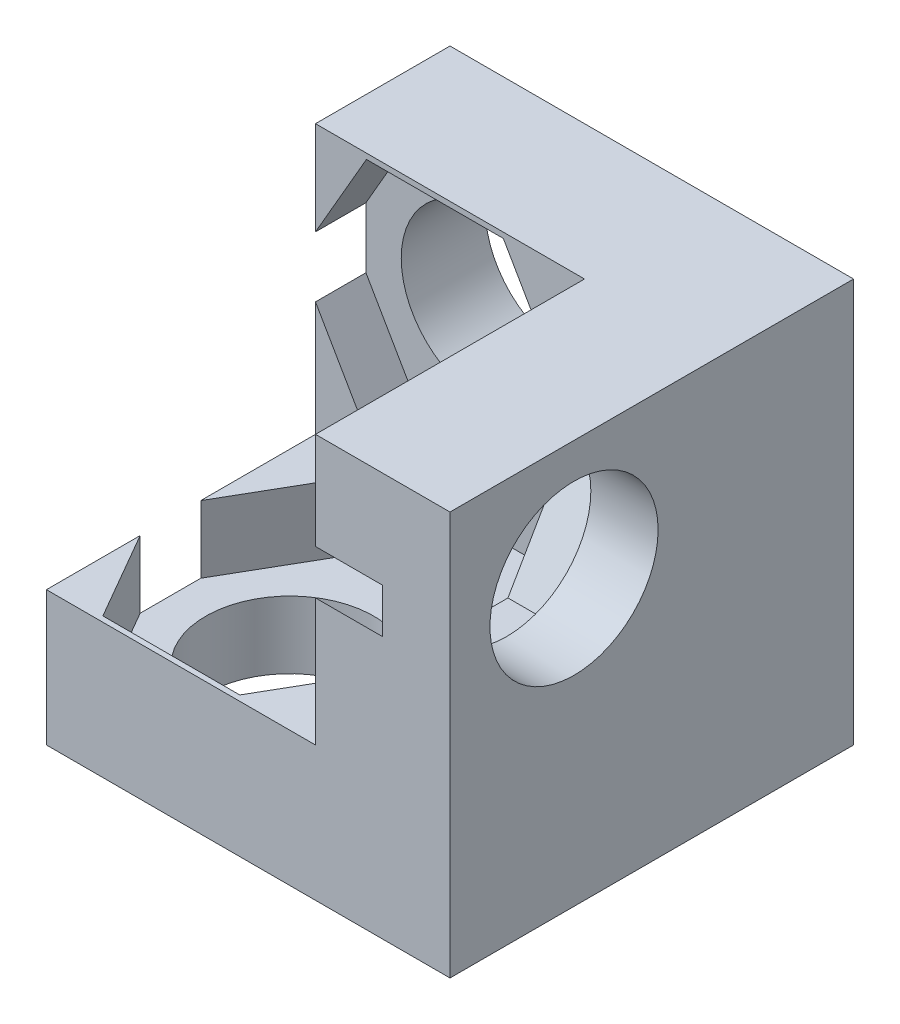
SolidWorks part; units mm, degrees
ref_plane "Front Plane" through (0, 0, 0) normal (0, 0, 1) x (1, 0, 0)
ref_plane "Top Plane" through (0, 0, 0) normal (0, 1, 0) x (1, 0, 0)
ref_plane "Right Plane" through (0, 0, 0) normal (1, 0, 0) x (0, 0, -1)
sketch "Sketch2" plane through (0, 0, 0) normal (0, 0, 1) x (1, 0, 0)
  line L0 (-6, 6) -> (-6, -2.4497)
  line L1 (-6, -6) -> (6, -6)
  line L2 (-6, -6) -> (-6, 6)
  line L3 (-6, 6) -> (6, 6)
  line L4 (6, -6) -> (6, 6)
  line L5 (-6, -6) -> (6, 6) construction
  line L6 (-6, 6) -> (6, -6) construction
  line L7 (-6, 6) -> (2.3122, 6)
  line L8 (2.3122, 6) -> (2.3122, -6)
  line L9 (-6, -2.4497) -> (6, -2.4497)
  circle A1 centre (2.3122, -2.4497) radius 2.05
  point P0 (0, 0)
  dimension "D4" = 4.1
  dimension "D1" = 8.3122
  dimension "D2" = 8.4497
  dimension "D3" = 12
extrude "Boss-Extrude1" add sketch "Sketch2" along normal blind 12 contours A1 L8 L3 L0 L9 | A1 L9 L4 L3 L8 | L9 A1 L8 | L8 A1 L9 | L9 A1 L8 | L8 A1 L9 | A1 L8 L1 L4 L9 | A1 L9 L2 L1 L8
sketch "Sketch3" plane through (0, 6, 0) normal (0, 1, 0) x (1, 0, 0)
  line L0 (-6, 0) -> (-6, -4)
  line L1 (-6, -12) -> (-6, 0) construction
  line L2 (-6, -4) -> (6, -4)
  line L3 (6, -12) -> (6, 0) construction
  line L4 (6, 0) -> (2, 0)
  line L5 (-6, 0) -> (6, 0) construction
  line L6 (2, 0) -> (2, -12)
  line L7 (-6, -12) -> (6, -12) construction
  line L9 (2, -4) -> (-6, -4)
  line L10 (2, -4) -> (2, -12)
  line L11 (2, -12) -> (-6, -12)
  line L12 (-6, -4) -> (-6, -12)
  line M3 (-6, 0) -> (-6, -12)
  line M4 (-6, -12) -> (6, -12)
  dimension "D1" = 4
extrude "Cut-Extrude1" cut sketch "Sketch3" against normal blind 8 contours L6 L2 M3 M4
sketch "Sketch6" plane through (0, -2, 0) normal (0, 1, 0) x (1, 0, 0)
  line L0 (6, 0) -> (-2.4497, 0)
  line L1 (-6, 0) -> (6, 0) construction
  line L2 (6, 0) -> (6, -8.3122)
  line L3 (6, -12) -> (6, 0) construction
  line L4 (-2.4497, 0.2353) -> (-2.4497, -12)
  line L5 (-6, -12) -> (2, -12) construction
  line L6 (6, -8.3122) -> (-6, -8.3122)
  line L7 (-6, -4) -> (-6, -12) construction
  circle A0 centre (-2.4497, -8.3122) radius 2.5
  dimension "D3" = 5
  dimension "D1" = 8.4497
  dimension "D2" = 8.3122
sketch "Sketch7" plane through (0, 0, 0) normal (0, 0, -1) x (-1, 0, 0)
  line L0 (-6, -6) -> (2.4497, -6)
  line L1 (6, -6) -> (-6, -6) construction
  line L2 (-6, -6) -> (-6, 2.3122)
  line L3 (-6, -6) -> (-6, 6) construction
  line L4 (-6, 2.3122) -> (6, 2.3122)
  line L5 (6, 6) -> (6, -6) construction
  line L6 (2.4497, -6) -> (2.4497, 6)
  line L7 (6, 6) -> (-6, 6) construction
  circle A0 centre (2.4497, 2.3122) radius 2.5
  dimension "D3" = 5
  dimension "D1" = 8.4497
  dimension "D2" = 8.3122
sketch "Sketch8" plane through (6, 0, 0) normal (1, 0, 0) x (0, 0, -1)
  line L0 (0, -6) -> (0, 2.4497)
  line L1 (0, -6) -> (0, 6) construction
  line L2 (0, -6) -> (-8.3122, -6)
  line L3 (-12, -6) -> (0, -6) construction
  line L4 (-8.3122, -6) -> (-8.3122, 6)
  line L5 (-12, 6) -> (0, 6) construction
  line L6 (0, 2.4497) -> (-12, 2.4497)
  line L7 (-12, -6) -> (-12, 6) construction
  circle A0 centre (-8.3122, 2.4497) radius 2.5
  dimension "D3" = 5
  dimension "D1" = 8.3122
  dimension "D2" = 8.4497
sketch "Sketch13" plane through (0, 6, 0) normal (0, 1, 0) x (1, 0, 0)
  line L0 (-6, 0) -> (-6, -4)
  line L1 (-6, -4) -> (2, -4)
  line L2 (2, -4) -> (2, -12)
  line L3 (2, -12) -> (6, -12)
  line L4 (6, -12) -> (6, 0)
  line L5 (6, 0) -> (-6, 0)
extrude "Cut-Extrude8" cut sketch "Sketch6" against normal through all contours L6 A0 L4 | L4 A0 L6 | L4 A0 L6 | L6 A0 L4
extrude "Cut-Extrude9" cut sketch "Sketch8" against normal through all contours A0
extrude "Cut-Extrude10" cut sketch "Sketch7" against normal through all contours L6 A0 L4 | L4 A0 L6 | L6 A0 L4 | L4 A0 L6
sketch "Sketch14" plane through (0, 0, 0) normal (0, 0, -1) x (-1, 0, 0)
  line L1 (6.5201, 2.3122) -> (4.4849, 5.8372)
  line L2 (4.4849, 5.8372) -> (0.4146, 5.8372)
  line L3 (0.4146, 5.8372) -> (-1.6206, 2.3122)
  line L4 (-1.6206, 2.3122) -> (0.4146, -1.2128)
  line L5 (0.4146, -1.2128) -> (4.4849, -1.2128)
  line L6 (4.4849, -1.2128) -> (6.5201, 2.3122)
  circle A0 centre (2.4497, 2.3122) radius 3.525 construction
  dimension "D1" = 7.05
extrude "Cut-Extrude11" cut sketch "Sketch14" against normal blind 10 from offset 2.5 offset against normal yes
sketch "Sketch15" plane through (0, -2, 0) normal (0, 1, 0) x (1, 0, 0)
  line L1 (1.6206, -8.3122) -> (-0.4146, -4.7872)
  line L2 (-0.4146, -4.7872) -> (-4.4849, -4.7872)
  line L3 (-4.4849, -4.7872) -> (-6.5201, -8.3122)
  line L4 (-6.5201, -8.3122) -> (-4.4849, -11.8372)
  line L5 (-4.4849, -11.8372) -> (-0.4146, -11.8372)
  line L6 (-0.4146, -11.8372) -> (1.6206, -8.3122)
  circle A0 centre (-2.4497, -8.3122) radius 3.525 construction
  dimension "D1" = 7.05
extrude "Cut-Extrude13" cut sketch "Sketch15" against normal blind 2
sketch "Sketch16" plane through (2, 0, 0) normal (-1, 0, 0) x (0, 0, 1)
  line L1 (12.3825, 2.4497) -> (10.3473, 5.9747)
  line L2 (10.3473, 5.9747) -> (6.277, 5.9747)
  line L3 (6.277, 5.9747) -> (4.2419, 2.4497)
  line L4 (4.2419, 2.4497) -> (6.277, -1.0753)
  line L5 (6.277, -1.0753) -> (10.3473, -1.0753)
  line L6 (10.3473, -1.0753) -> (12.3825, 2.4497)
  circle A0 centre (8.3122, 2.4497) radius 3.525 construction
  dimension "D1" = 7.05
extrude "Cut-Extrude14" cut sketch "Sketch16" against normal blind 2
